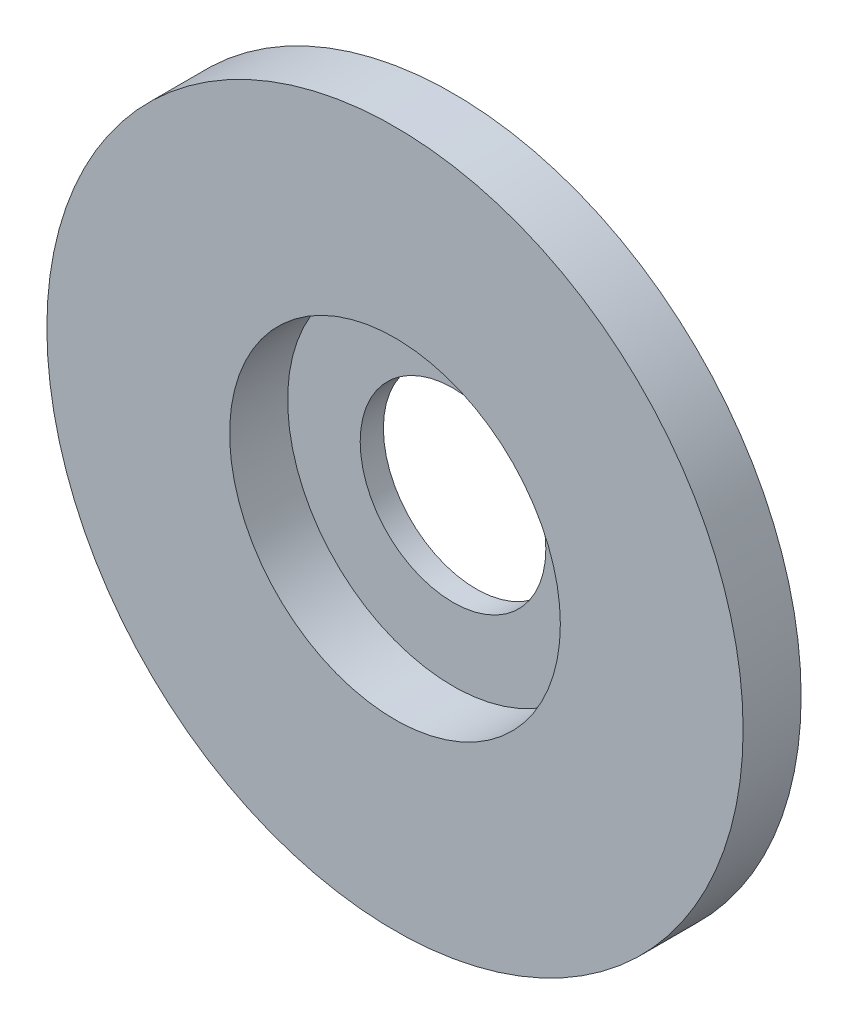
SolidWorks part; units mm, degrees
ref_plane "Front Plane" through (0, 0, 0) normal (0, 0, 1) x (1, 0, 0)
ref_plane "Top Plane" through (0, 0, 0) normal (0, 1, 0) x (1, 0, 0)
ref_plane "Right Plane" through (0, 0, 0) normal (1, 0, 0) x (0, 0, -1)
sketch "Sketch2" plane through (0, 0, 0) normal (0, 0, 1) x (1, 0, 0)
  circle A0 centre (0, 0) radius 30
  circle A1 centre (0, 0) radius 8
  dimension "D1" = 16
extrude "Boss-Extrude1" add sketch "Sketch2" along normal blind 2
sketch "Sketch3" plane through (0, 0, 2) normal (0, 0, 1) x (1, 0, 0)
  circle A0 centre (0, 0) radius 14.25
  circle A1 centre (0, 0) radius 30
extrude "Boss-Extrude2" add sketch "Sketch3" along normal blind 5
sketch "Sketch4" plane through (0, 0, 0) normal (0, 0, -1) x (-1, 0, 0)
  circle A0 centre (0, 0) radius 8 construction
  circle A1 centre (0, 0) radius 30
  circle A2 centre (0, 0) radius 30
  circle A3 centre (0, 0) radius 8
  dimension "D1" = 0
sketch "Sketch5" plane through (0, 0, 2) normal (0, 0, 1) x (1, 0, 0)
  circle A0 centre (0, 0) radius 8 construction
  circle A1 centre (0, 0) radius 14.25
  circle A2 centre (0, 0) radius 14.25
  circle A3 centre (0, 0) radius 8
  dimension "D1" = 0
extrude "Cut-Extrude1" cut sketch "Sketch5" against normal blind 1
sketch "Sketch7" plane through (0, 0, 7) normal (0, 0, 1) x (1, 0, 0)
  circle A0 centre (0, 0) radius 30 construction
  circle A1 centre (0, 0) radius 30
  circle A2 centre (0, 0) radius 14.25 construction
  circle A3 centre (0, 0) radius 14.25
extrude "Boss-Extrude4" add sketch "Sketch7" along normal blind 1
sketch "Sketch8" plane through (0, 0, 8) normal (0, 0, 1) x (1, 0, 0)
  circle A0 centre (0, 0) radius 14.25 construction
  circle A1 centre (0, 0) radius 30
  circle A2 centre (0, 0) radius 30
  circle A3 centre (0, 0) radius 14.25
  dimension "D1" = 0
extrude "Cut-Extrude3" cut sketch "Sketch8" against normal blind 2
sketch "Sketch10" plane through (0, 0, 0) normal (0, 0, -1) x (-1, 0, 0)
  circle A0 centre (0, 0) radius 8 construction
  circle A1 centre (0, 0) radius 8
  circle A2 centre (0, 0) radius 20
extrude "Boss-Extrude6" add sketch "Sketch10" along normal blind 1
sketch "Sketch11" plane through (0, 0, 0) normal (0, 0, -1) x (-1, 0, 0)
  circle A0 centre (0, 0) radius 20 construction
  circle A1 centre (0, 0) radius 30
  circle A2 centre (0, 0) radius 30
  circle A3 centre (0, 0) radius 20
  dimension "D1" = 0
extrude "Cut-Extrude4" cut sketch "Sketch11" against normal blind 1
